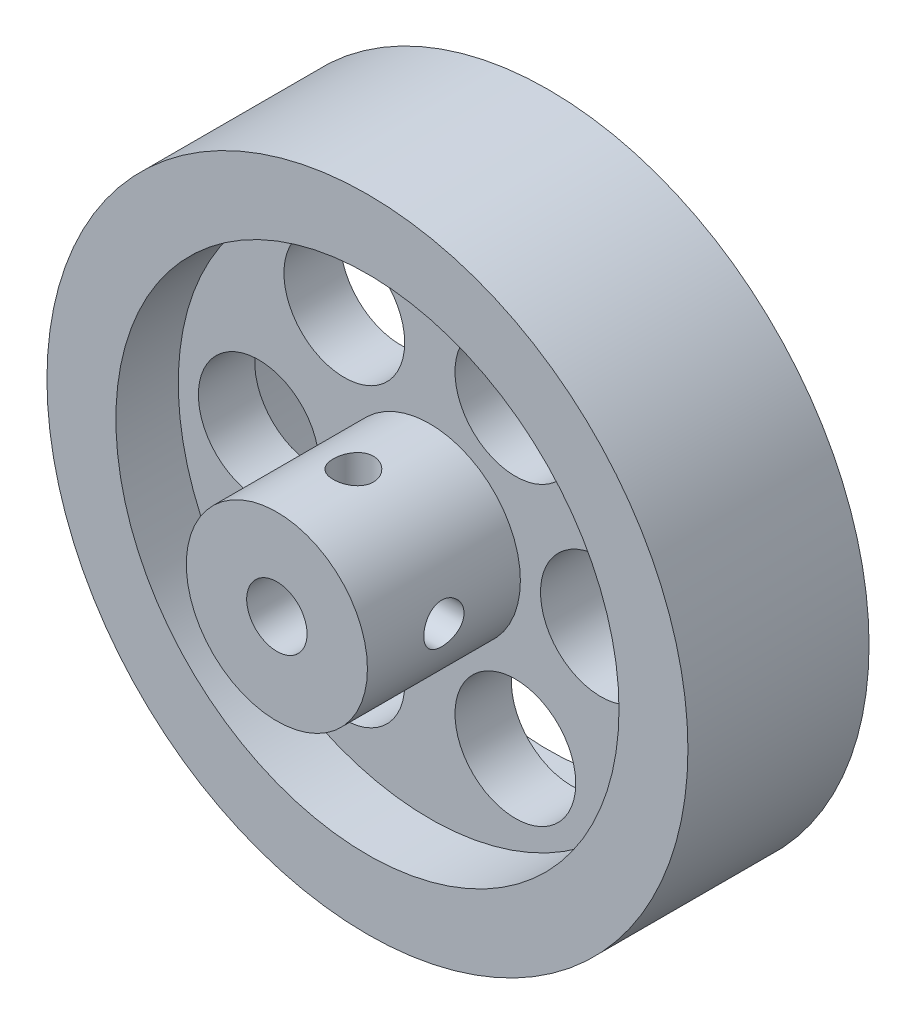
SolidWorks part; units mm, degrees
ref_plane "前视基准面" through (0, 0, 0) normal (0, 0, 1) x (1, 0, 0)
ref_plane "上视基准面" through (0, 0, 0) normal (0, 1, 0) x (1, 0, 0)
ref_plane "右视基准面" through (0, 0, 0) normal (1, 0, 0) x (0, 0, -1)
other "Configuration Table"
sketch "草图1" plane through (0, 0, 0) normal (0, 0, 1) x (1, 0, 0)
  circle A0 centre (0, 0) radius 31.85
  dimension "D1" = 63.7
extrude "凸台-拉伸1" add sketch "草图1" along normal blind 18
sketch "草图2" plane through (0, 0, 18) normal (0, 0, 1) x (1, 0, 0)
  circle A0 centre (0, 0) radius 25
  circle A1 centre (0, 0) radius 9
  circle A2 centre (0, 0) radius 3
  dimension "D1" = 50
  dimension "D2" = 18
  dimension "D3" = 6
extrude "切除-拉伸1" cut sketch "草图2" against normal blind 6.2 contours A0 A1
sketch "草图3" plane through (0, 0, 0) normal (0, 0, -1) x (-1, 0, 0)
  circle A0 centre (0, 0) radius 9 construction
  circle A1 centre (0, 0) radius 31.85
  circle A2 centre (0, 0) radius 31.85
  circle A3 centre (0, 0) radius 25 construction
  circle A4 centre (0, 0) radius 9
  circle A5 centre (0, 0) radius 25
  dimension "D1" = 0
extrude "切除-拉伸5" cut sketch "草图3" against normal blind 6.2 contours A5 | A4
sketch "草图4" plane through (0, 0, 18) normal (0, 0, 1) x (1, 0, 0)
  circle A1 centre (0, 0) radius 9
  circle A2 centre (0, 0) radius 9
  dimension "D1" = 0
extrude "凸台-拉伸2" add sketch "草图4" along normal blind 9
sketch "草图5" plane through (0, 0, 27) normal (0, 0, 1) x (1, 0, 0)
  circle A0 centre (0, 0) radius 3
  dimension "D1" = 6
extrude "切除-拉伸6" cut sketch "草图5" against normal through all
sketch "草图6" plane through (0, 0, 11.8) normal (0, 0, 1) x (1, 0, 0)
  line L0 (-17, 0) -> (0, 0)
  circle A0 centre (-17, 0) radius 6
  circle A1 centre (-8.5, 14.7224) radius 6
  circle A2 centre (8.5, 14.7224) radius 6
  circle A3 centre (17, 0) radius 6
  circle A4 centre (8.5, -14.7224) radius 6
  circle A5 centre (-8.5, -14.7224) radius 6
  point P5 (18.9189, -5.0593)
  point P6 (0, 0)
  point P16 (0, 0)
  dimension "D1" = 12
  dimension "D2" = 17
  dimension "D3" = 6
extrude "切除-拉伸7" cut sketch "草图6" against normal through all
ref_plane "基准面1" through (9, 0, 0) normal (1, 0, 0) x (0, 0, -1)
sketch "草图7" plane through (9, 0, 0) normal (1, 0, 0) x (0, 0, -1)
  line L0 (-27, 9) -> (-27, -9) construction
  line L1 (-11.8, 9) -> (-11.8, -9) construction
  line L2 (-27, 9) -> (-27, -9)
  line L3 (-11.8, 9) -> (-11.8, -9)
  line L4 (-27, 0) -> (-11.8, 0)
  line L5 (-11.8, 9) -> (-11.8, -9)
  line L6 (-27, 9) -> (-27, -9)
  line L7 (-11.8, 9) -> (-11.8, -9)
  line L8 (-27, 9) -> (-27, -9)
  circle A0 centre (-19.4, 0) radius 2
  dimension "D1" = 4
ref_plane "基准面2" through (0, 9, 0) normal (0, 1, 0) x (1, 0, 0)
sketch "草图10" plane through (0, 9, 0) normal (0, 1, 0) x (1, 0, 0)
  line L0 (-9, -11.8) -> (9, -11.8) construction
  line L1 (-9, -27) -> (9, -27) construction
  line L2 (-9, -11.8) -> (9, -11.8)
  line L3 (-9, -27) -> (9, -27)
  line L5 (0, -11.8) -> (0, -27)
  circle A0 centre (0, -19.4) radius 2
  dimension "D1" = 4
extrude "切除-拉伸10" cut sketch "草图10" against normal up to next contours A0
extrude "切除-拉伸11" cut sketch "草图7" against normal up to next contours A0
